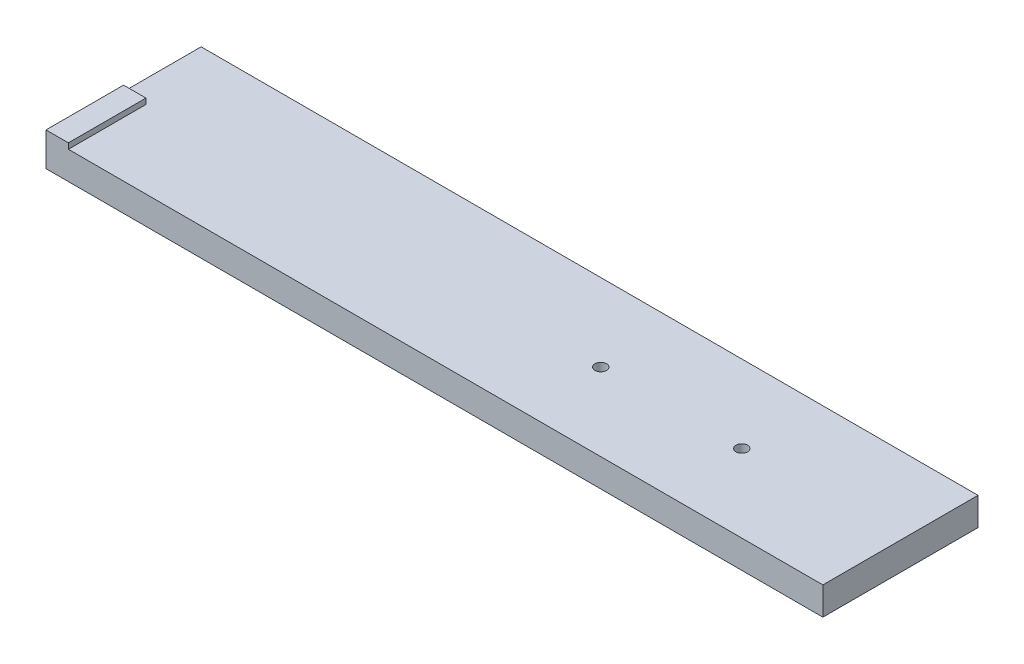
SolidWorks part; units mm, degrees
material "6061 Alloy"
ref_plane "Front" through (0, 0, 0) normal (0, 0, 1) x (1, 0, 0)
ref_plane "Top" through (0, 0, 0) normal (0, 1, 0) x (1, 0, 0)
ref_plane "Right" through (0, 0, 0) normal (1, 0, 0) x (0, 0, -1)
sketch "Sketch1" plane through (0, 0, 0) normal (0, 1, 0) x (1, 0, 0)
  line L1 (0, 0) -> (220.35, 0)
  line L2 (0, 0) -> (0, 44)
  line L3 (0, 44) -> (220.35, 44)
  line L4 (220.35, 0) -> (220.35, 44)
  dimension "D1" = 44
  dimension "D2" = 220.35
extrude "Boss-Extrude1" add sketch "Sketch1" along normal blind 7.9375
sketch "Sketch2" plane through (0, 7.9375, 0) normal (0, 1, 0) x (1, 0, 0)
  line L1 (0, 0) -> (6.35, 0)
  line L2 (0, 0) -> (0, 22)
  line L3 (0, 22) -> (6.35, 22)
  line L4 (6.35, 0) -> (6.35, 22)
  line L5 (0, 0) -> (220.35, 0) construction
  point P7 (0, 0)
  dimension "D1" = 6.35
  dimension "D2" = 22
extrude "Boss-Extrude2" add sketch "Sketch2" along normal blind 1.5875
hole_wizard "M4x0.7 Tapped Hole2" positions "Sketch5" profile "Sketch6" tap size "M4x0.7" standard "ANSI Metric" end condition through all
sketch "Sketch5" plane through (0, 7.9375, 0) normal (0, 1, 0) x (1, 0, 0)
  line L0 (220.35, 22) -> (135.35, 22) construction
  line L1 (220.35, 0) -> (220.35, 44) construction
  point P0 (135.35, 22)
  point P2 (175.35, 22)
  dimension "D1" = 85
  dimension "D2" = 40
sketch "Sketch6" plane through (135.35, 7.9375, -22) normal (1, 0, 0) x (0, 0, 1)
  line L0 (0, 0) -> (0, 7.9375)
  line L1 (0, 7.9375) -> (1.65, 7.9375)
  line L2 (1.65, 7.9375) -> (1.65, 0)
  line L5 (1.65, 0) -> (0, 0)
  line L11 (0, -6.35) -> (0, 107.95) construction
  dimension "Thru Tap Drill Dia." = 3.3
  dimension "Thru Tap Drill Depth" = 7.9375
cosmetic thread "Hole Thread1" parameters "D2"=4
cosmetic thread "Hole Thread2" parameters "D2"=4
